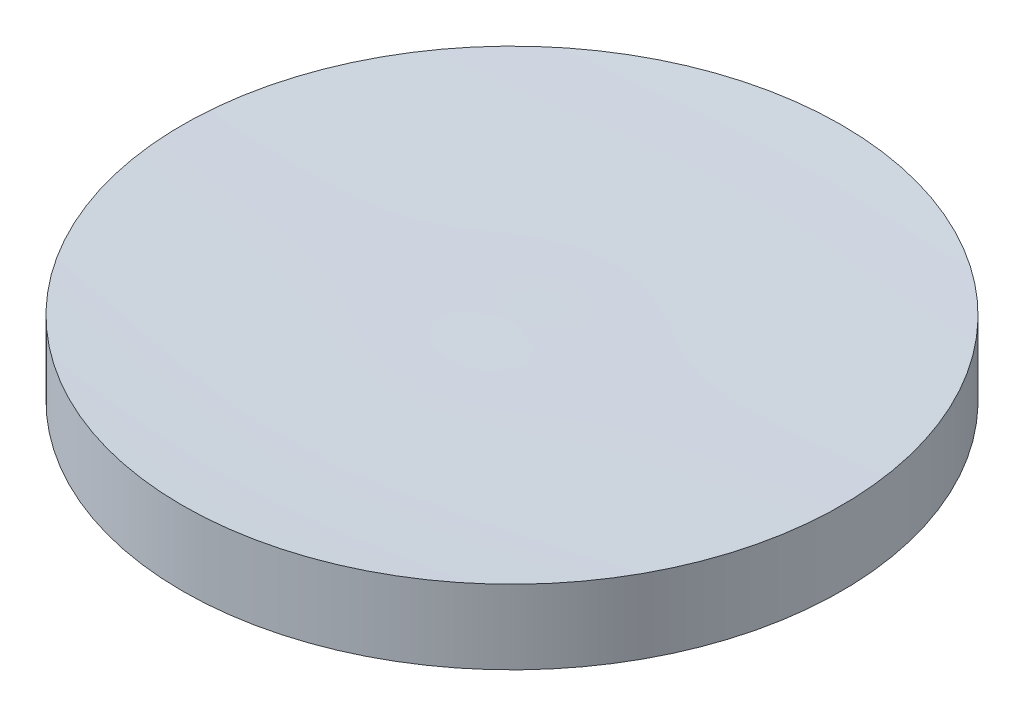
SolidWorks part; units mm, degrees
ref_plane "Спереди" through (0, 0, 0) normal (0, 0, 1) x (1, 0, 0)
ref_plane "Сверху" through (0, 0, 0) normal (0, 1, 0) x (1, 0, 0)
ref_plane "Справа" through (0, 0, 0) normal (1, 0, 0) x (0, 0, -1)
sketch "Эскиз1" plane through (0, 0, 0) normal (0, 1, 0) x (1, 0, 0)
  circle A0 centre (0, 0) radius 80
  dimension "D1" = 160
extrude "Бобышка-Вытянуть1" add sketch "Эскиз1" along normal blind 18
sketch "Эскиз3" plane through (0, 0, 0) normal (1, 0, 0) x (0, 0, -1)
  line L0 (80, 18) -> (-80, 18) construction
  line L1 (-80, 18) -> (-80, 0) construction
  line L2 (0, 16.77) -> (0, 18)
  line L3 (0, 18) -> (-80, 18)
  arc A1 (0, 16.77) -> (-80, 18) centre (-20.1012, 1311.614) cw
  point P5 (0, 0)
  point P8 (0, 15.5266)
  dimension "D1" = 1295
  dimension "D2" = 1.23
revolve "Вырез-Повернуть1" cut sketch "Эскиз3" angle 360 about L2
sketch "Эскиз4" plane through (0, 0, 0) normal (0, -1, 0) x (1, 0, 0)
  line L1 (-90, -90) -> (90, -90)
  line L3 (-80, 0) -> (-90, 0)
  line L4 (-90, 0) -> (-90, -90)
  line L5 (80, 0) -> (90, 0)
  line L6 (90, 0) -> (90, -90)
  circle A0 centre (0, 0) radius 80 construction
  arc A1 (-80, 0) -> (80, 0) centre (0, 0) ccw
  dimension "D1" = 90
  dimension "D2" = 180
